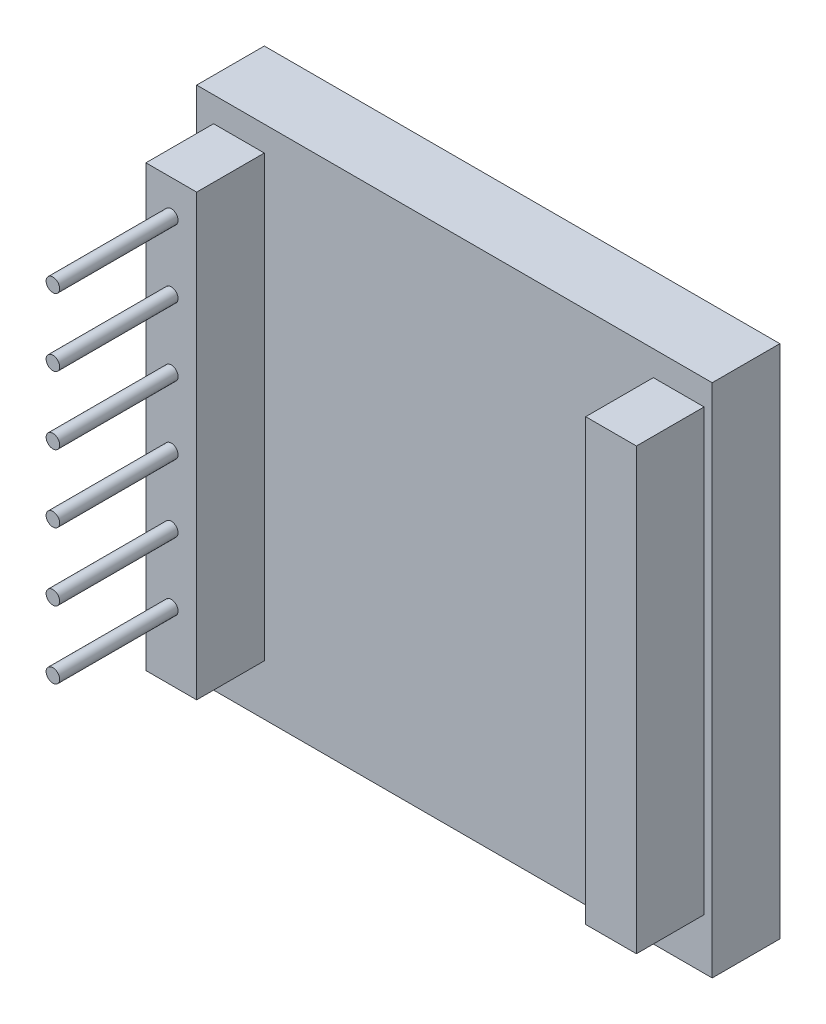
SolidWorks part; units mm, degrees
ref_plane "前视基准面" through (0, 0, 0) normal (0, 0, 1) x (1, 0, 0)
ref_plane "上视基准面" through (0, 0, 0) normal (0, 1, 0) x (1, 0, 0)
ref_plane "右视基准面" through (0, 0, 0) normal (1, 0, 0) x (0, 0, -1)
sketch "草图1" plane through (0, 0, 0) normal (0, 0, 1) x (1, 0, 0)
  line L1 (0, 0) -> (15.24, 0)
  line L2 (0, 0) -> (0, 15.24)
  line L3 (0, 15.24) -> (15.24, 15.24)
  line L4 (15.24, 0) -> (15.24, 15.24)
  dimension "D1" = 15.24
  dimension "D2" = 15.24
extrude "凸台-拉伸1" add sketch "草图1" along normal blind 2
sketch "草图2" plane through (0, 0, 2) normal (0, 0, 1) x (1, 0, 0)
  line L1 (13.5, 14.5) -> (15, 14.5)
  line L2 (13.5, 14.5) -> (13.5, 1.5)
  line L3 (13.5, 1.5) -> (15, 1.5)
  line L4 (15, 14.5) -> (15, 1.5)
  line L5 (0.5, 14.5) -> (2, 14.5)
  line L6 (0.5, 14.5) -> (0.5, 1.5)
  line L7 (0.5, 1.5) -> (2, 1.5)
  line L8 (2, 14.5) -> (2, 1.5)
extrude "凸台-拉伸2" add sketch "草图2" along normal blind 2
sketch "草图3" plane through (0, 0, 4) normal (0, 0, 1) x (1, 0, 0)
  circle A0 centre (1.25, 13.5) radius 0.2
  circle A7 centre (1.25, 11.5) radius 0.2
  circle A8 centre (1.25, 9.5) radius 0.2
  circle A9 centre (1.25, 7.5) radius 0.2
  circle A10 centre (1.25, 5.5) radius 0.2
  circle A11 centre (1.25, 3.5) radius 0.2
  circle A12 centre (14.25, 13.5) radius 0.2 [skipped]
  circle A13 centre (14.25, 11.5) radius 0.2 [skipped]
  circle A14 centre (14.25, 9.5) radius 0.2 [skipped]
  circle A15 centre (14.25, 7.5) radius 0.2 [skipped]
  circle A16 centre (14.25, 5.5) radius 0.2 [skipped]
  circle A17 centre (14.25, 3.5) radius 0.2 [skipped]
  dimension "D1" = 2
  dimension "D2" = 6
extrude "凸台-拉伸3" add sketch "草图3" along normal blind 3.5 and the other way blind 4.5
